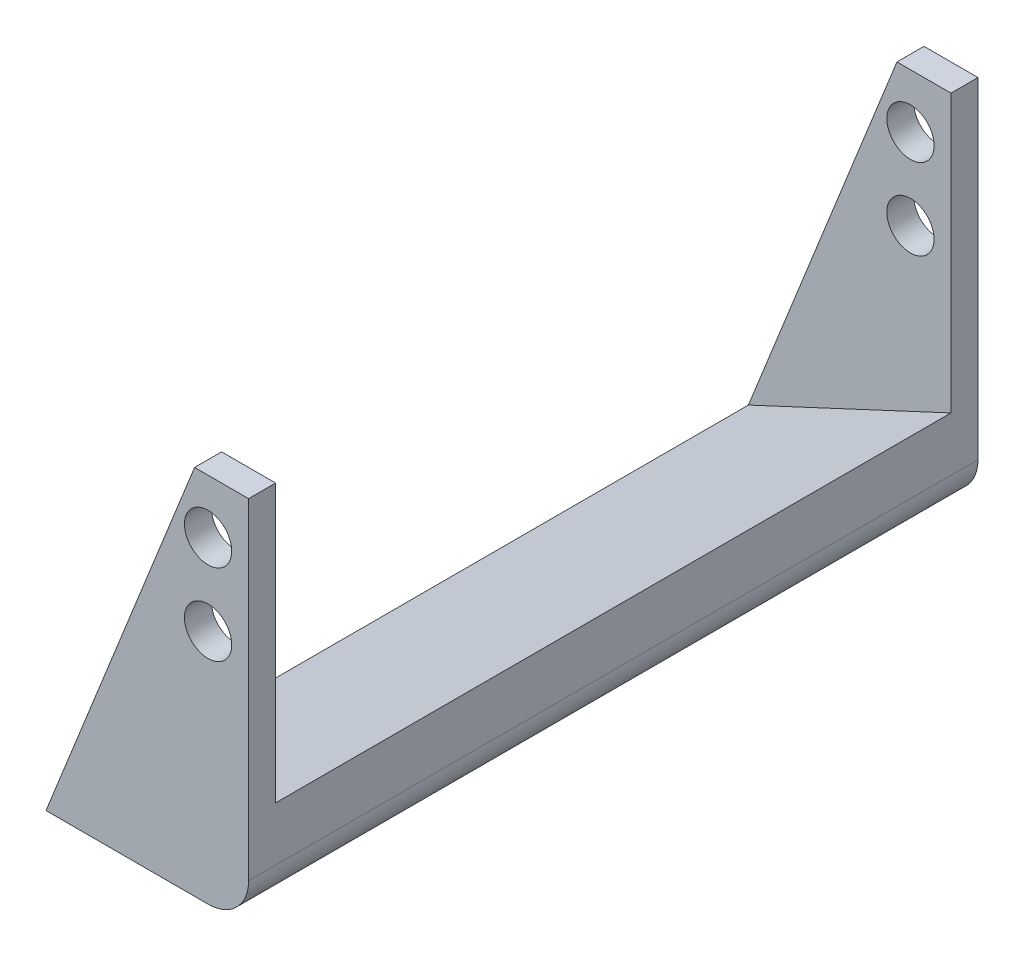
SolidWorks part; units mm, degrees
ref_plane "Front Plane" through (0, 0, 0) normal (0, 0, 1) x (1, 0, 0)
ref_plane "Top Plane" through (0, 0, 0) normal (0, 1, 0) x (1, 0, 0)
ref_plane "Right Plane" through (0, 0, 0) normal (1, 0, 0) x (0, 0, -1)
sketch "Sketch1" plane through (0, 0, 0) normal (0, 0, 1) x (1, 0, 0)
  line L0 (0, 0) -> (15, 0)
  line L1 (15, 0) -> (15, 6.9946)
  line L2 (15, 6.9946) -> (0, 0)
  dimension "D1" = 25
  dimension "D2" = 15
extrude "Boss-Extrude1" add sketch "Sketch1" along normal mid plane 50
sketch "Sketch2" plane through (0, 0, 25) normal (0, 0, 1) x (1, 0, 0)
  line L0 (15, 0) -> (15, 27.5)
  line L1 (15, 27.5) -> (11, 27.5)
  line L2 (11, 27.5) -> (0, 0)
  line L3 (0, 0) -> (15, 0)
  line L4 (12, 27.5) -> (12, 23.5) construction
  line L5 (12, 23.5) -> (12, 17.5) construction
  circle A0 centre (12, 23.5) radius 1.75
  circle A1 centre (12, 17.5) radius 1.75
  dimension "D5" = 3.5
  dimension "D1" = 27.5
  dimension "D2" = 4
  dimension "D3" = 4
  dimension "D4" = 6
  dimension "D6" = 3
extrude "Boss-Extrude2" add sketch "Sketch2" along normal blind 2
mirror "Mirror1" about plane through (0, 0, 0) normal (0, 0, 1) of "Boss-Extrude2"
fillet "Fillet1" radius 3 1 edges at (15, 0, 0)
